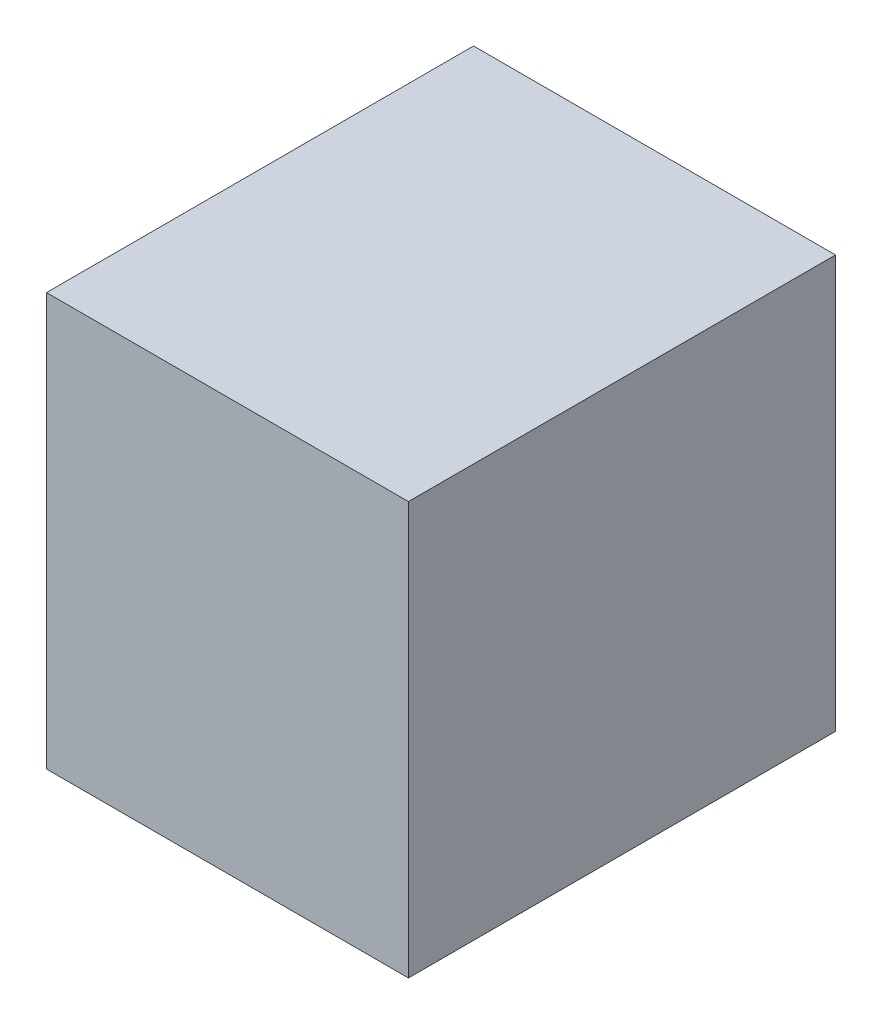
SolidWorks part; units mm, degrees
ref_plane "前基準面" through (0, 0, 0) normal (0, 0, 1) x (1, 0, 0)
ref_plane "上基準面" through (0, 0, 0) normal (0, 1, 0) x (1, 0, 0)
ref_plane "右基準面" through (0, 0, 0) normal (1, 0, 0) x (0, 0, -1)
sketch "草圖1" plane through (0, 0, 0) normal (0, 0, 1) x (1, 0, 0)
  line L1 (-306.9728, 258.658) -> (193.0272, 258.658)
  line L2 (-306.9728, 258.658) -> (-306.9728, -311.342)
  line L3 (-306.9728, -311.342) -> (193.0272, -311.342)
  line L4 (193.0272, 258.658) -> (193.0272, -311.342)
  dimension "D1" = 570
  dimension "D2" = 500
extrude "填料-伸長1" add sketch "草圖1" along normal blind 590
